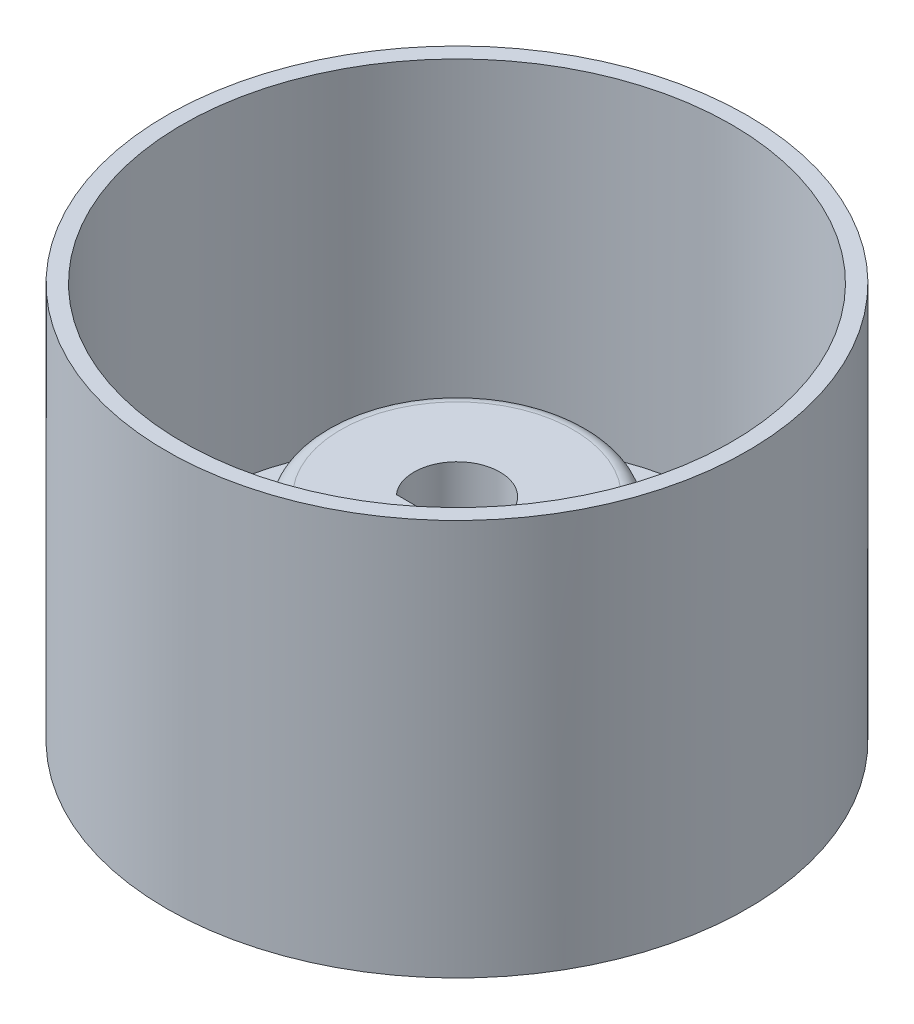
SolidWorks part; units mm, degrees
ref_plane "Front Plane" through (0, 0, 0) normal (0, 0, 1) x (1, 0, 0)
ref_plane "Top Plane" through (0, 0, 0) normal (0, 1, 0) x (1, 0, 0)
ref_plane "Right Plane" through (0, 0, 0) normal (1, 0, 0) x (0, 0, -1)
sketch "Sketch1" plane through (0, 0, 0) normal (0, 1, 0) x (1, 0, 0)
  circle A0 centre (0, 0) radius 11
  dimension "D1" = 22
extrude "Boss-Extrude1" add sketch "Sketch1" along normal blind 2.5
sketch "Sketch2" plane through (0, 2.5, 0) normal (0, 1, 0) x (1, 0, 0)
  circle A0 centre (0, 0) radius 5
  dimension "D1" = 10
extrude "Boss-Extrude2" add sketch "Sketch2" along normal blind 5.5
sketch "Sketch3" plane through (0, 2.5, 0) normal (0, 1, 0) x (1, 0, 0)
  line L0 (0, 11) -> (0, 8) construction
  circle A0 centre (0, 8) radius 1.53
  circle A1 centre (0, 0) radius 11 construction
  circle A2 centre (6.9282, -4) radius 1.53
  circle A3 centre (-6.9282, -4) radius 1.53
  point P11 (0, 0)
  dimension "D2" = 3.06
  dimension "D1" = 3
  dimension "D3" = 3
extrude "Cut-Extrude1" cut sketch "Sketch3" against normal through all
sketch "Sketch4" plane through (0, 8, 0) normal (0, 1, 0) x (1, 0, 0)
  line L0 (-1.2186, -1.075) -> (1.2186, -1.075)
  line L1 (0, 1.625) -> (0, -1.075) construction
  arc A0 (1.2186, -1.075) -> (-1.2186, -1.075) centre (0, 0) ccw
  dimension "3.3" = 3.25
  dimension "D2" = 2.7
extrude "Cut-Extrude2" cut sketch "Sketch4" against normal through all
fillet "Fillet1" radius 0.6 2 edges at (0, 8, 5) (0, 2.5, 5)
sketch "Sketch5" plane through (0, 0, 0) normal (0, -1, 0) x (1, 0, 0)
  circle A0 centre (0, 0) radius 11 construction
  circle A1 centre (0, 0) radius 11
  circle A2 centre (0, 0) radius 10.4
  dimension "D1" = 0.6
extrude "Boss-Extrude3" add sketch "Sketch5" against normal blind 15
